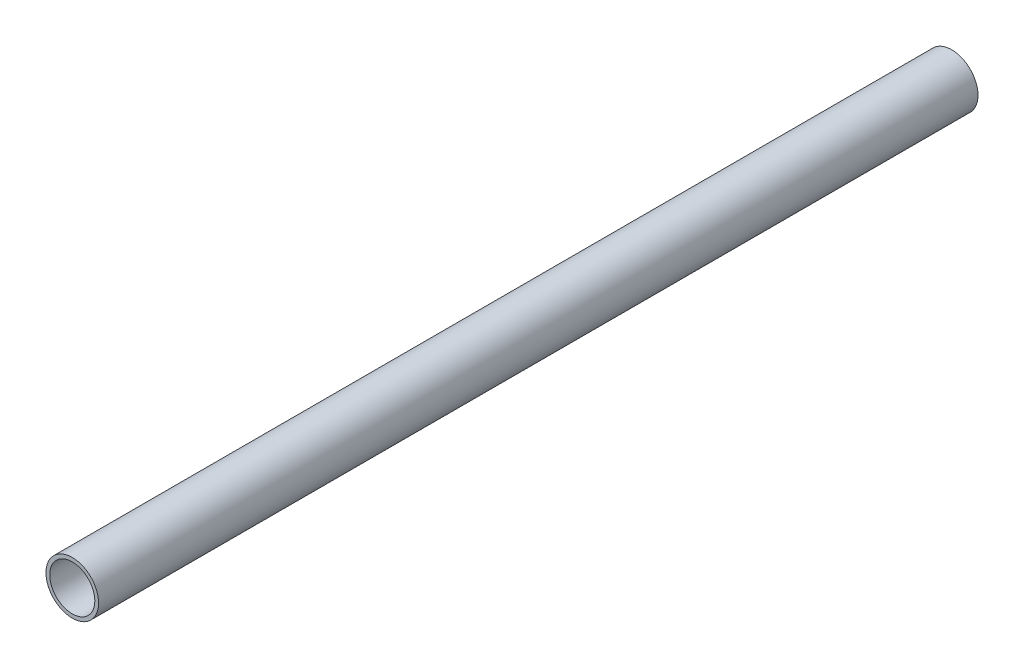
SolidWorks part; units mm, degrees
other "Arm"
ref_plane "Front Plane" through (0, 0, 0) normal (0, 0, 1) x (1, 0, 0)
ref_plane "Top Plane" through (0, 0, 0) normal (0, 1, 0) x (1, 0, 0)
ref_plane "Right Plane" through (0, 0, 0) normal (1, 0, 0) x (0, 0, -1)
sketch "Arm Cross-Section Sketch" plane through (0, 0, 0) normal (0, 0, 1) x (1, 0, 0)
  circle A0 centre (0, 0) radius 7
  circle A1 centre (0, 0) radius 6
extrude "Arm Extrude" add sketch "Arm Cross-Section Sketch" along normal blind 234 contours A0 | A1
